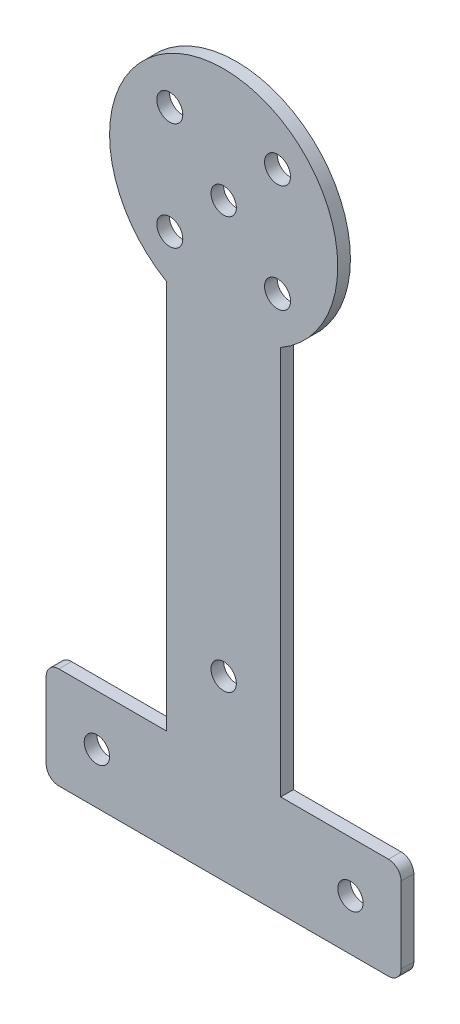
SolidWorks part; units mm, degrees
ref_plane "前视基准面" through (0, 0, 0) normal (0, 0, 1) x (1, 0, 0)
ref_plane "上视基准面" through (0, 0, 0) normal (0, 1, 0) x (1, 0, 0)
ref_plane "右视基准面" through (0, 0, 0) normal (1, 0, 0) x (0, 0, -1)
sketch "草图1" plane through (0, 0, 0) normal (0, 0, 1) x (1, 0, 0)
  line L2 (-13.3404, 27.5655) -> (-13.3404, 112.5655) construction
  line L3 (-13.3404, 112.5655) -> (-7.3404, 112.5655) construction
  line L6 (14.6596, 19.5655) -> (14.6596, 35.5655)
  line L9 (-41.3404, 19.5655) -> (-41.3404, 35.5655)
  line L11 (-41.3404, 35.5655) -> (-22.3404, 35.5655)
  line L14 (-33.3404, 27.5655) -> (-13.3404, 27.5655) construction
  line L15 (-13.3404, 27.5655) -> (6.6596, 27.5655) construction
  line L16 (-4.3404, 35.5655) -> (14.6596, 35.5655)
  line L17 (-41.3404, 19.5655) -> (14.6596, 19.5655)
  line L18 (-13.3404, 112.5655) -> (-13.3404, 121.0655) construction
  line L19 (-13.3404, 121.0655) -> (-4.8404, 121.0655) construction
  line L20 (-4.3404, 35.5655) -> (-4.3404, 96.9771)
  line L21 (-22.3404, 35.5655) -> (-22.3404, 96.9771)
  circle A4 centre (-33.3404, 27.5655) radius 2
  circle A5 centre (6.6596, 27.5655) radius 2
  circle A9 centre (-13.3404, 112.5655) radius 2
  circle A12 centre (-13.3404, 47.5655) radius 2
  circle A13 centre (-4.8404, 121.0655) radius 2.05
  circle A14 centre (-4.8404, 104.0655) radius 2.05
  circle A15 centre (-21.8404, 104.0655) radius 2.05
  circle A16 centre (-21.8404, 121.0655) radius 2.05
  circle A17 centre (-13.3404, 112.5655) radius 18 construction
  arc A18 (-22.3404, 96.9771) -> (-4.3404, 96.9771) centre (-13.3404, 112.5655) cw
  dimension "D5" = 4
  dimension "D7" = 4
  dimension "D8" = 65
  dimension "D2" = 20
  dimension "D3" = 8
  dimension "D4" = 8
  dimension "D9" = 8
  dimension "D10" = 20
  dimension "D11" = 20
  dimension "D12" = 8
extrude "凸台-拉伸1" add sketch "草图1" along normal blind 2
fillet "圆角1" radius 2 4 edges at (14.6596, 35.5655, 1) (14.6596, 19.5655, 1) (-41.3404, 19.5655, 1) (-41.3404, 35.5655, 1)
